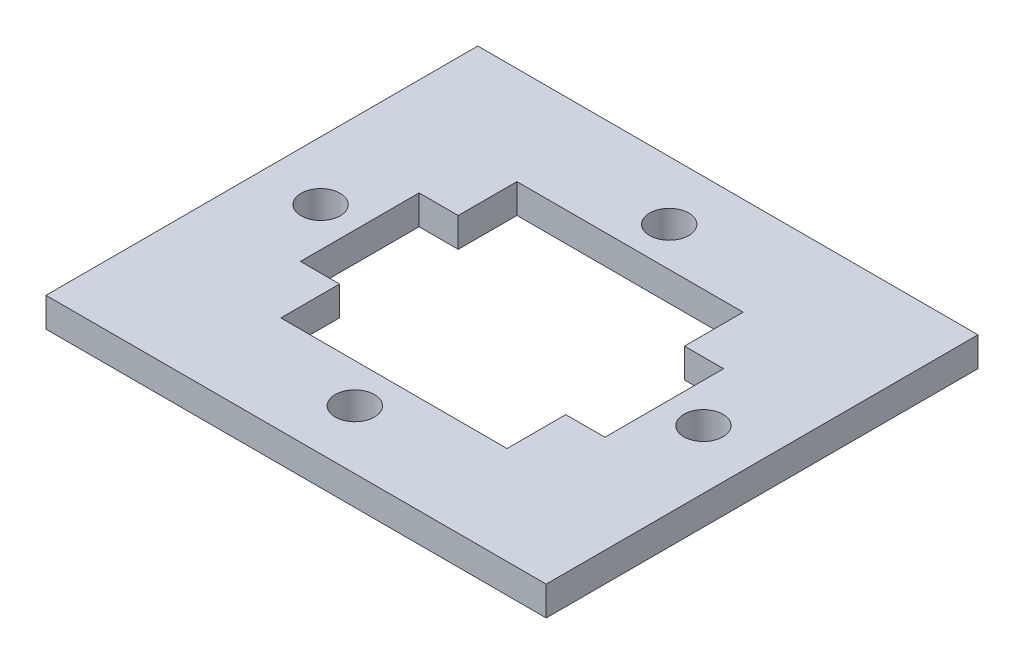
SolidWorks part; units mm, degrees
ref_plane "Plano frontal" through (0, 0, 0) normal (0, 0, 1) x (1, 0, 0)
ref_plane "Plano superior" through (0, 0, 0) normal (0, 1, 0) x (1, 0, 0)
ref_plane "Plano direito" through (0, 0, 0) normal (1, 0, 0) x (0, 0, -1)
sketch "Esboço1" plane through (0, 0, 0) normal (0, 1, 0) x (1, 0, 0)
  line L0 (23.12, 24.13) -> (23.12, 18.13)
  line L5 (-14, -10) -> (37.12, -10)
  line L6 (-14, -10) -> (-14, 34.13)
  line L7 (-14, 34.13) -> (37.12, 34.13)
  line L8 (37.12, -10) -> (37.12, 34.13)
  line L9 (23.12, 18.13) -> (27.12, 18.13)
  line L10 (27.12, 6) -> (23.12, 6)
  line L11 (23.12, 6) -> (23.12, 0)
  line L12 (-4, 6) -> (0, 6)
  line L13 (0, 6) -> (0, 0)
  line L14 (0, 24.13) -> (0, 18.13)
  line L15 (0, 18.13) -> (-4, 18.13)
  line L16 (27.12, 18.13) -> (27.12, 6)
  line L17 (23.12, 0) -> (0, 0)
  line L18 (-4, 6) -> (-4, 18.13)
  line L19 (0, 24.13) -> (23.12, 24.13)
  circle A0 centre (31.12, 12.065) radius 2
  circle A1 centre (-8, 12.065) radius 2
  circle A2 centre (11.56, 28.13) radius 2
  circle A3 centre (11.56, -4) radius 2
  point P0 (11.56, 24.13)
  point P1 (27.12, 12.065)
  point P2 (-4, 12.065)
  point P3 (11.56, 0)
  dimension "D7" = 4
  dimension "D8" = 4
  dimension "D9" = 4
  dimension "D10" = 4
  dimension "D2" = 6
  dimension "D3" = 4
  dimension "D4" = 31.12
  dimension "D5" = 24.13
  dimension "D6" = 4
  dimension "D11" = 6
  dimension "D12" = 10
  dimension "D13" = 10
  dimension "D14" = 10
  dimension "D15" = 10
  dimension "D16" = 4
  dimension "D17" = 4
  dimension "D18" = 4
  dimension "D19" = 4
extrude "Ressalto-extrusão1" add sketch "Esboço1" along normal blind 3
